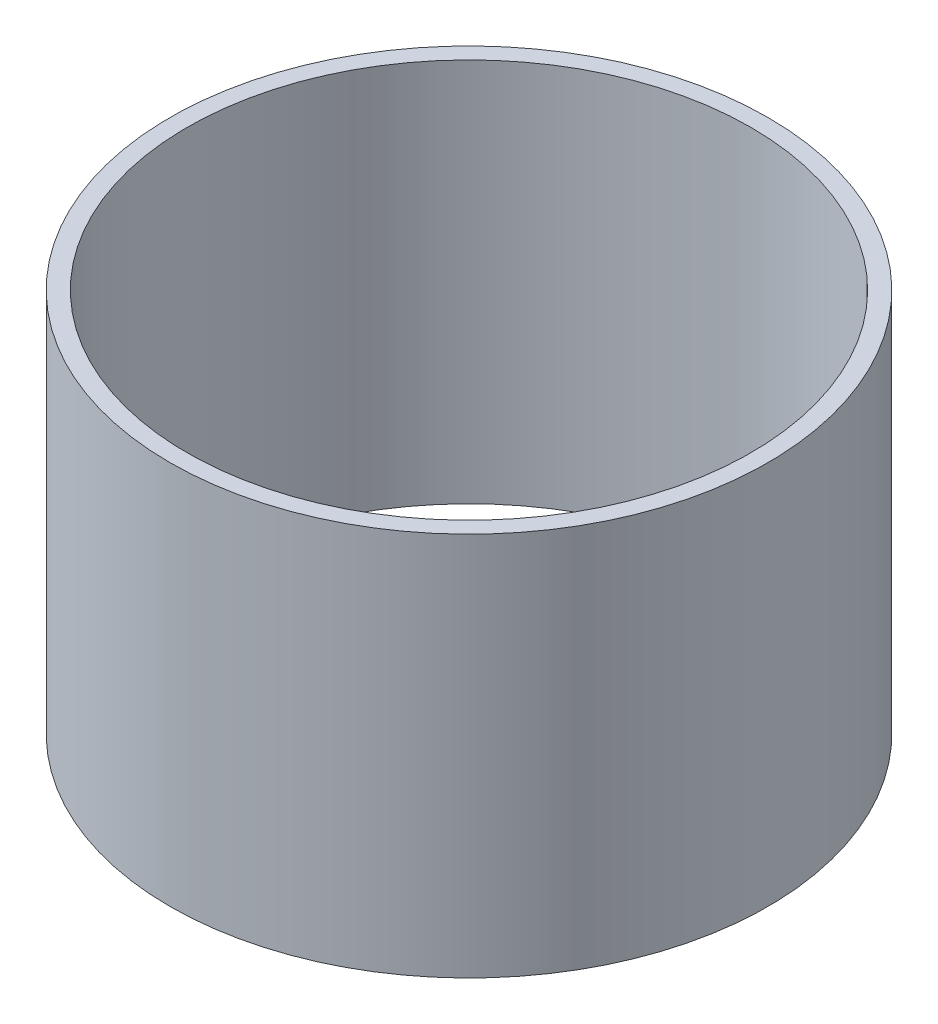
SolidWorks part; units mm, degrees
ref_plane "Front Plane" through (0, 0, 0) normal (0, 0, 1) x (1, 0, 0)
ref_plane "Top Plane" through (0, 0, 0) normal (0, 1, 0) x (1, 0, 0)
ref_plane "Right Plane" through (0, 0, 0) normal (1, 0, 0) x (0, 0, -1)
sketch "Sketch1" plane through (0, 0, 0) normal (0, 1, 0) x (1, 0, 0)
  circle A0 centre (0, 0) radius 70
  circle A1 centre (0, 0) radius 66
  dimension "D1" = 140
  dimension "D2" = 4
extrude "Boss-Extrude1" add sketch "Sketch1" along normal blind 90
